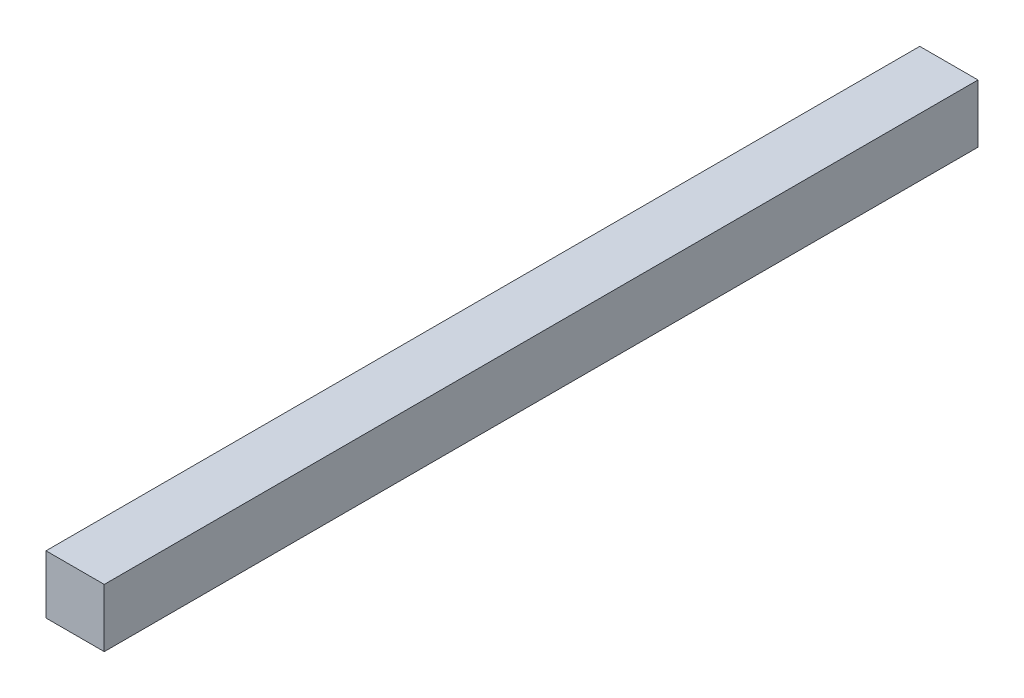
SolidWorks part; units mm, degrees
ref_plane "Front Plane" through (0, 0, 0) normal (0, 0, 1) x (1, 0, 0)
ref_plane "Top Plane" through (0, 0, 0) normal (0, 1, 0) x (1, 0, 0)
ref_plane "Right Plane" through (0, 0, 0) normal (1, 0, 0) x (0, 0, -1)
sketch "Sketch1" plane through (0, 0, 0) normal (0, 0, 1) x (1, 0, 0)
  line L1 (0, 0) -> (10, 0)
  line L2 (0, 0) -> (0, 10)
  line L3 (0, 10) -> (10, 10)
  line L4 (10, 0) -> (10, 10)
  dimension "D1" = 10
extrude "Boss-Extrude1" add sketch "Sketch1" along normal blind 150
